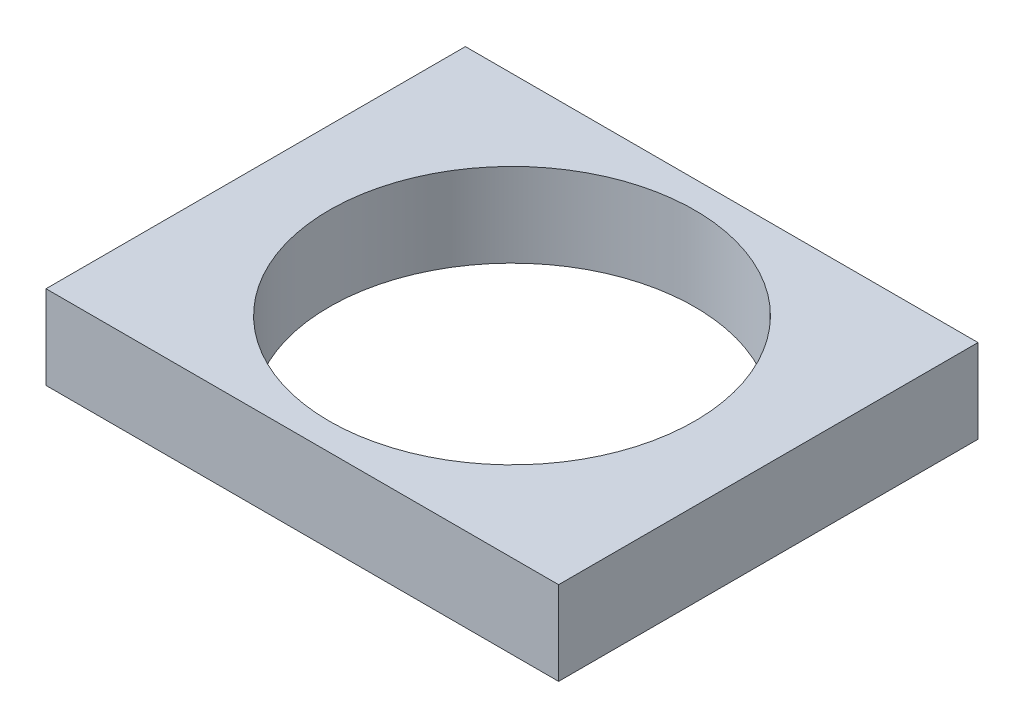
SolidWorks part; units mm, degrees
ref_plane "Front Plane" through (0, 0, 0) normal (0, 0, 1) x (1, 0, 0)
ref_plane "Top Plane" through (0, 0, 0) normal (0, 1, 0) x (1, 0, 0)
ref_plane "Right Plane" through (0, 0, 0) normal (1, 0, 0) x (0, 0, -1)
sketch "Sketch1" plane through (0, 0, 0) normal (0, 1, 0) x (1, 0, 0)
  line L1 (-51.0542, 17.9782) -> (10.1314, 17.9782)
  line L2 (-51.0542, 17.9782) -> (-51.0542, -32.0827)
  line L3 (-51.0542, -32.0827) -> (10.1314, -32.0827)
  line L4 (10.1314, 17.9782) -> (10.1314, -32.0827)
  circle A0 centre (-20.4614, -7.0522) radius 21.814
extrude "Boss-Extrude1" add sketch "Sketch1" along normal blind 10
